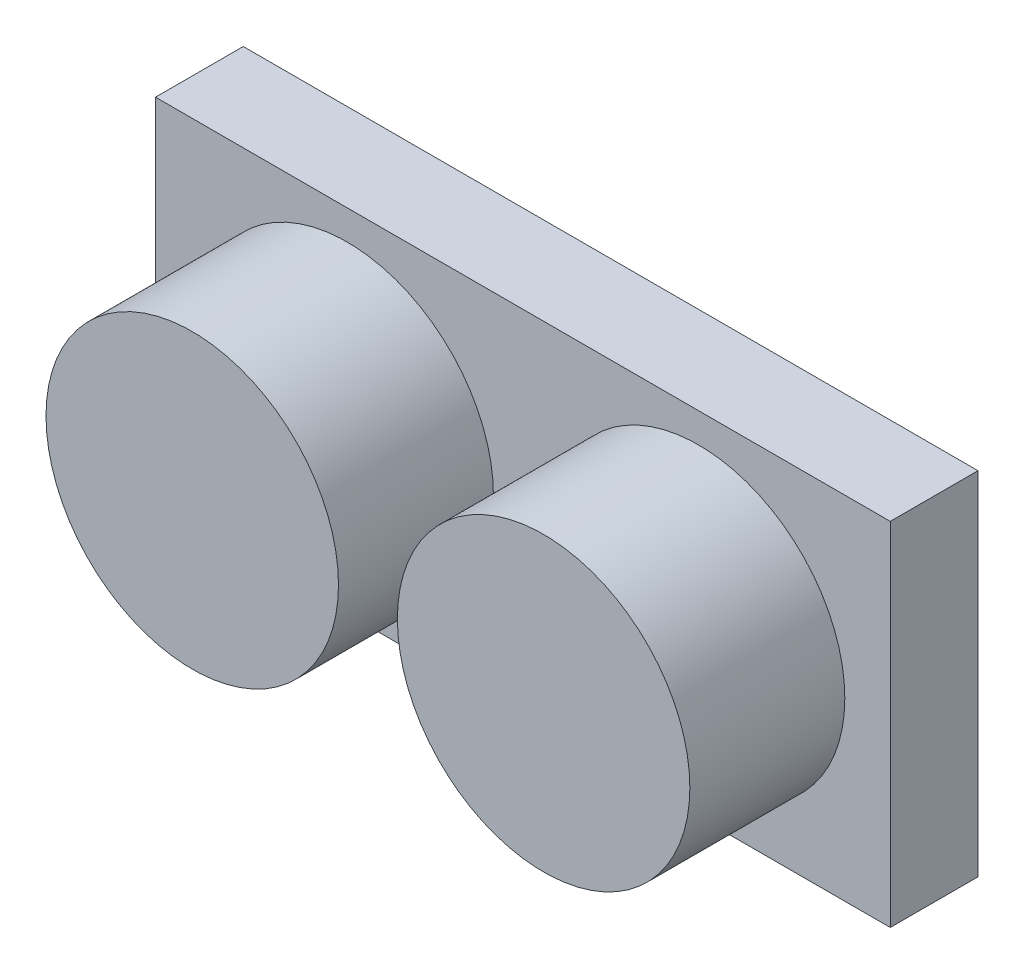
SolidWorks part; units mm, degrees
ref_plane "前视基准面" through (0, 0, 0) normal (0, 0, 1) x (1, 0, 0)
ref_plane "上视基准面" through (0, 0, 0) normal (0, 1, 0) x (1, 0, 0)
ref_plane "右视基准面" through (0, 0, 0) normal (1, 0, 0) x (0, 0, -1)
sketch "草图3" plane through (0, 0, 0) normal (0, 0, 1) x (1, 0, 0)
  line L1 (12.5601, -6.0128) -> (-12.5601, -6.0128)
  line L2 (12.5601, -6.0128) -> (12.5601, 6.0128)
  line L3 (12.5601, 6.0128) -> (-12.5601, 6.0128)
  line L4 (-12.5601, -6.0128) -> (-12.5601, 6.0128)
  line L5 (12.5601, -6.0128) -> (-12.5601, 6.0128) construction
  line L6 (12.5601, 6.0128) -> (-12.5601, -6.0128) construction
  point P0 (0, 0)
extrude "凸台-拉伸1" add sketch "草图3" along normal blind 3
sketch "草图4" plane through (0, 0, 3) normal (0, 0, 1) x (1, 0, 0)
  line L0 (0, -4.2047) -> (0, 4.9522) construction
  circle A0 centre (6.0067, 0) radius 5
  circle A1 centre (-6.0067, 0) radius 5
extrude "凸台-拉伸2" add sketch "草图4" along normal blind 5.2979
